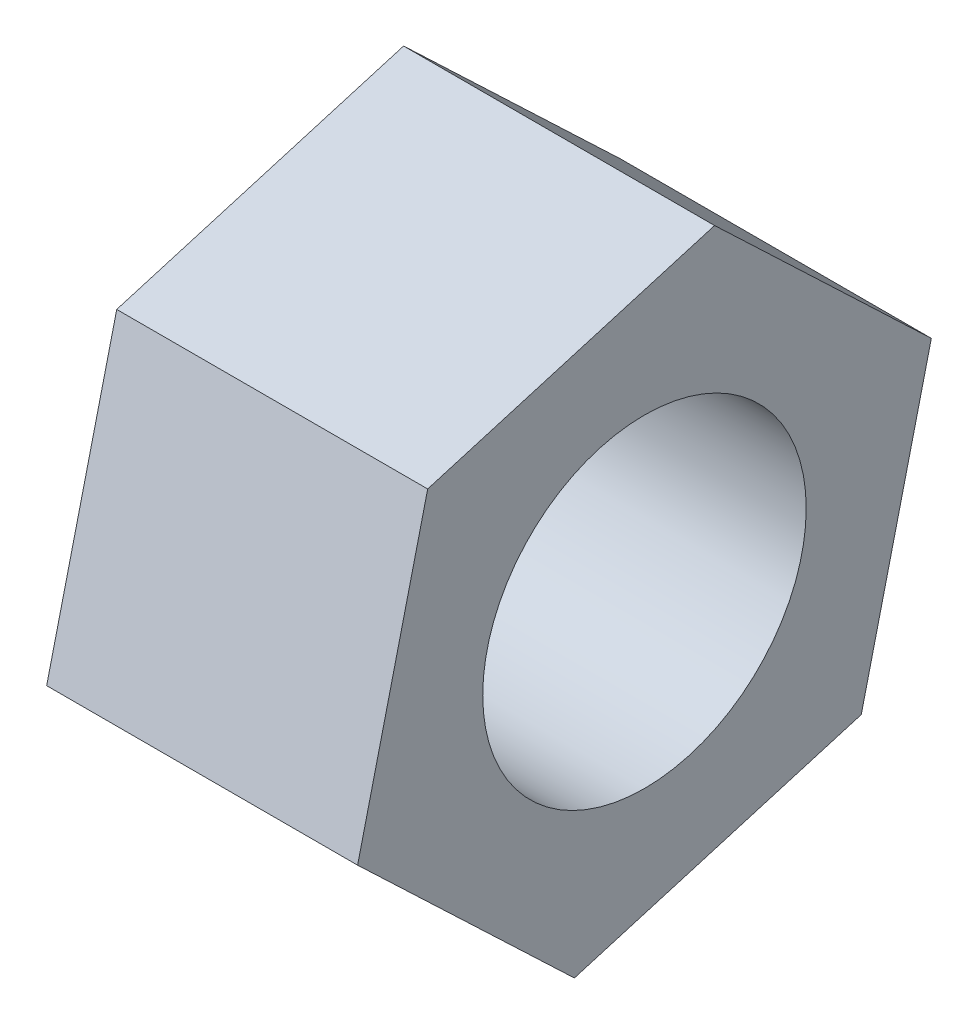
SolidWorks part; units mm, degrees
ref_plane "Front Plane" through (0, 0, 0) normal (0, 0, 1) x (1, 0, 0)
ref_plane "Top Plane" through (0, 0, 0) normal (0, 1, 0) x (1, 0, 0)
ref_plane "Right Plane" through (0, 0, 0) normal (1, 0, 0) x (0, 0, -1)
other "Configuration Table"
sketch "Sketch1" plane through (0, 0, 0) normal (1, 0, 0) x (0, 0, -1)
  line L1 (4.1552, -3.95) -> (5.4984, 1.6235)
  line L2 (5.4984, 1.6235) -> (1.3433, 5.5735)
  line L3 (1.3433, 5.5735) -> (-4.1552, 3.95)
  line L4 (-4.1552, 3.95) -> (-5.4984, -1.6235)
  line L5 (-5.4984, -1.6235) -> (-1.3433, -5.5735)
  line L6 (-1.3433, -5.5735) -> (4.1552, -3.95)
  circle A0 centre (0, 0) radius 4.965 construction
  point P1 (1.3433, 5.5735)
  dimension "D1" = 9.93
extrude "Boss-Extrude1" add sketch "Sketch1" along normal blind 5.96
sketch "Sketch2" plane through (5.96, 0, 0) normal (1, 0, 0) x (0, 0, -1)
  circle A0 centre (0, 0) radius 3.1
  dimension "D1" = 6.2
extrude "Cut-Extrude1" cut sketch "Sketch2" against normal through all
